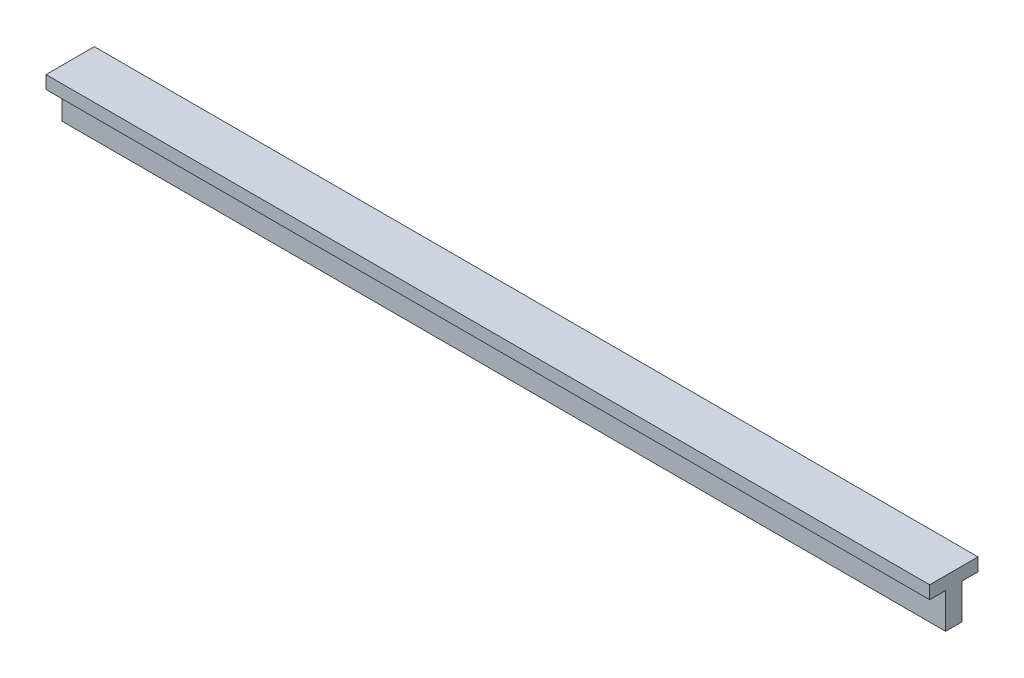
SolidWorks part; units mm, degrees
ref_plane "Front Plane" through (0, 0, 0) normal (0, 0, 1) x (1, 0, 0)
ref_plane "Top Plane" through (0, 0, 0) normal (0, 1, 0) x (1, 0, 0)
ref_plane "Right Plane" through (0, 0, 0) normal (1, 0, 0) x (0, 0, -1)
sketch "Sketch1" plane through (0, 0, 0) normal (1, 0, 0) x (0, 0, -1)
  line L0 (55, -22) -> (82, -22)
  line L1 (0, 0) -> (82, 0)
  line L2 (0, 0) -> (0, -22)
  line L3 (0, -22) -> (27, -22)
  line L4 (82, 0) -> (82, -22)
  line L6 (55, -22) -> (55, -82)
  line L7 (55, -82) -> (27, -82)
  line L8 (27, -22) -> (27, -82)
  point P9 (41, -82)
  point P10 (41, 0)
  dimension "D1" = 22
  dimension "D2" = 82
  dimension "D3" = 28
  dimension "D4" = 60
extrude "Boss-Extrude1" add sketch "Sketch1" along normal blind 1500 contours L0 L4 L1 L2 L3 L8 L7 L6
